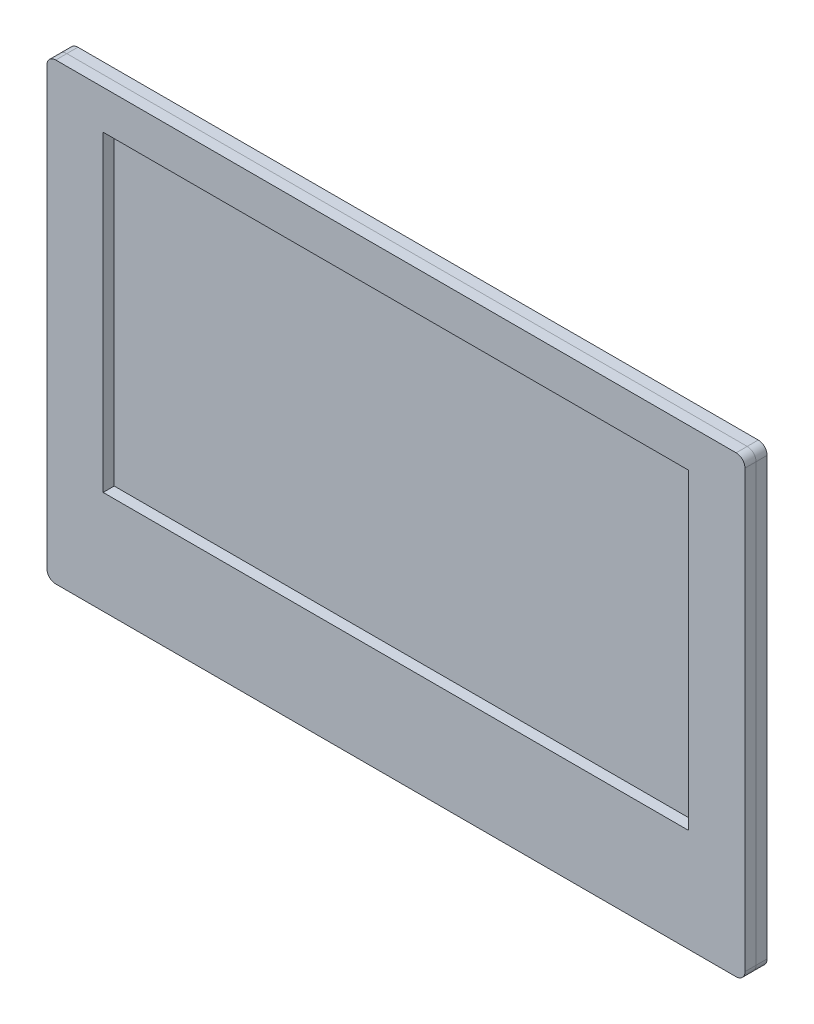
SolidWorks part; units mm, degrees
ref_plane "Front Plane" through (0, 0, 0) normal (0, 0, 1) x (1, 0, 0)
ref_plane "Top Plane" through (0, 0, 0) normal (0, 1, 0) x (1, 0, 0)
ref_plane "Right Plane" through (0, 0, 0) normal (1, 0, 0) x (0, 0, -1)
sketch "Sketch1" plane through (0, 0, 0) normal (0, 0, 1) x (1, 0, 0)
  line L0 (0, 44.7422) -> (0, 55.8825) construction
  line L1 (-83.9851, -44.7422) -> (83.9851, -44.7422)
  line L2 (-83.9851, -44.7422) -> (-83.9851, 44.7422)
  line L3 (-83.9851, 44.7422) -> (83.9851, 44.7422)
  line L4 (83.9851, -44.7422) -> (83.9851, 44.7422)
  line L5 (-83.9851, -44.7422) -> (83.9851, 44.7422) construction
  line L6 (-83.9851, 44.7422) -> (83.9851, -44.7422) construction
  line L7 (-100.1155, 55.8825) -> (100.1155, 55.8825)
  line L8 (-100.1155, 55.8825) -> (-100.1155, -74.2822)
  line L9 (-100.1155, -74.2822) -> (100.1155, -74.2822)
  line L10 (100.1155, 55.8825) -> (100.1155, -74.2822)
  point P0 (0, 0)
  dimension "D1" = 167.9702
  dimension "D2" = 89.4845
extrude "Boss-Extrude1" add sketch "Sketch1" along normal mid plane 3.175
fillet "Fillet1" radius 2.54 4 edges at (100.1155, -74.2822, 0) (-100.1155, -74.2822, 0) (100.1155, 55.8825, 0) (-100.1155, 55.8825, 0)
sketch "Sketch2" plane through (0, 0, -1.5875) normal (0, 0, -1) x (-1, 0, 0)
  line L4 (100.1155, -71.7422) -> (100.1155, 53.3425)
  line L5 (97.5755, 55.8825) -> (-97.5755, 55.8825)
  line L6 (-100.1155, 53.3425) -> (-100.1155, -71.7422)
  line L7 (-97.5755, -74.2822) -> (97.5755, -74.2822)
  line L8 (100.1155, -71.7422) -> (100.1155, 53.3425)
  line L9 (97.5755, 55.8825) -> (-97.5755, 55.8825)
  line L10 (-100.1155, 53.3425) -> (-100.1155, -71.7422)
  line L11 (-97.5755, -74.2822) -> (97.5755, -74.2822)
  arc A4 (-100.1155, -71.7422) -> (-97.5755, -74.2822) centre (-97.5755, -71.7422) ccw
  arc A5 (-100.1155, -71.7422) -> (-97.5755, -74.2822) centre (-97.5755, -71.7422) ccw
  arc A6 (97.5755, -74.2822) -> (100.1155, -71.7422) centre (97.5755, -71.7422) ccw
  arc A7 (97.5755, -74.2822) -> (100.1155, -71.7422) centre (97.5755, -71.7422) ccw
  arc A8 (100.1155, 53.3425) -> (97.5755, 55.8825) centre (97.5755, 53.3425) ccw
  arc A9 (100.1155, 53.3425) -> (97.5755, 55.8825) centre (97.5755, 53.3425) ccw
  arc A10 (-97.5755, 55.8825) -> (-100.1155, 53.3425) centre (-97.5755, 53.3425) ccw
  arc A11 (-97.5755, 55.8825) -> (-100.1155, 53.3425) centre (-97.5755, 53.3425) ccw
  dimension "D1" = 0
extrude "Boss-Extrude2" add sketch "Sketch2" along normal blind 3.175 separate body
